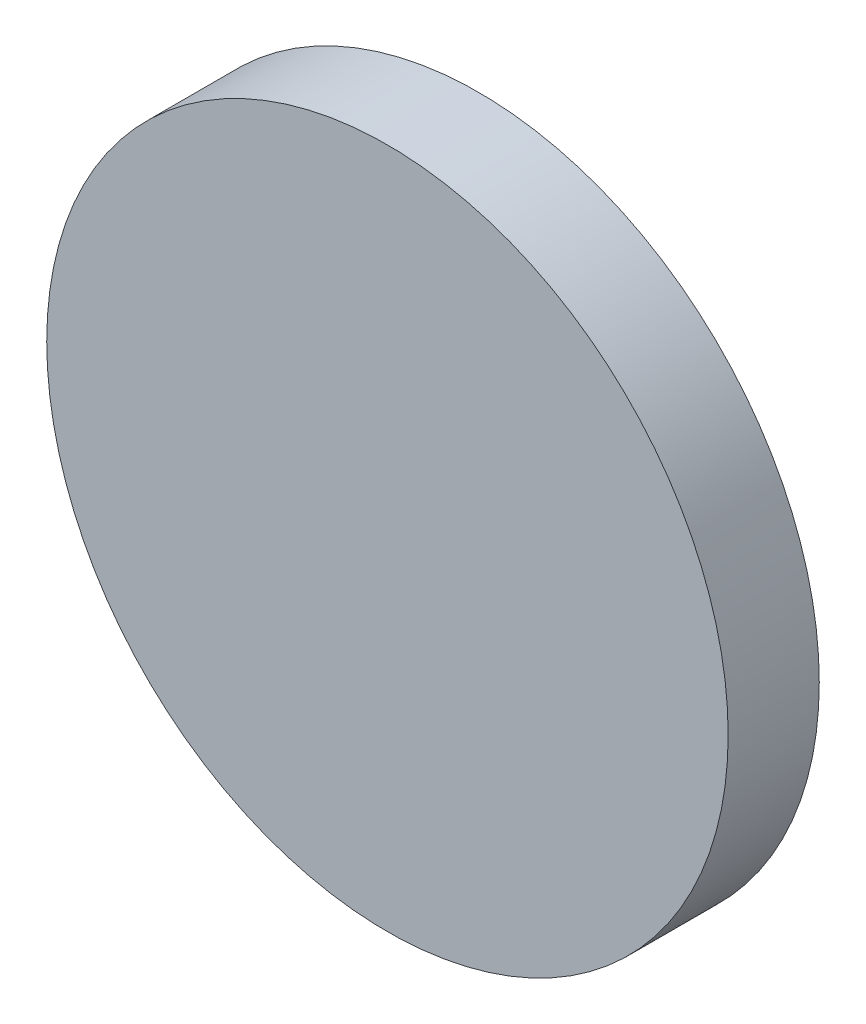
SolidWorks part; units mm, degrees
ref_plane "Front Plane" through (0, 0, 0) normal (0, 0, 1) x (1, 0, 0)
ref_plane "Top Plane" through (0, 0, 0) normal (0, 1, 0) x (1, 0, 0)
ref_plane "Right Plane" through (0, 0, 0) normal (1, 0, 0) x (0, 0, -1)
sketch "Sketch1" plane through (0, 0, 0) normal (0, 0, 1) x (1, 0, 0)
  circle A2 centre (0, 0) radius 11.8745
extrude "Boss-Extrude1" add sketch "Sketch1" along normal blind 3.175
